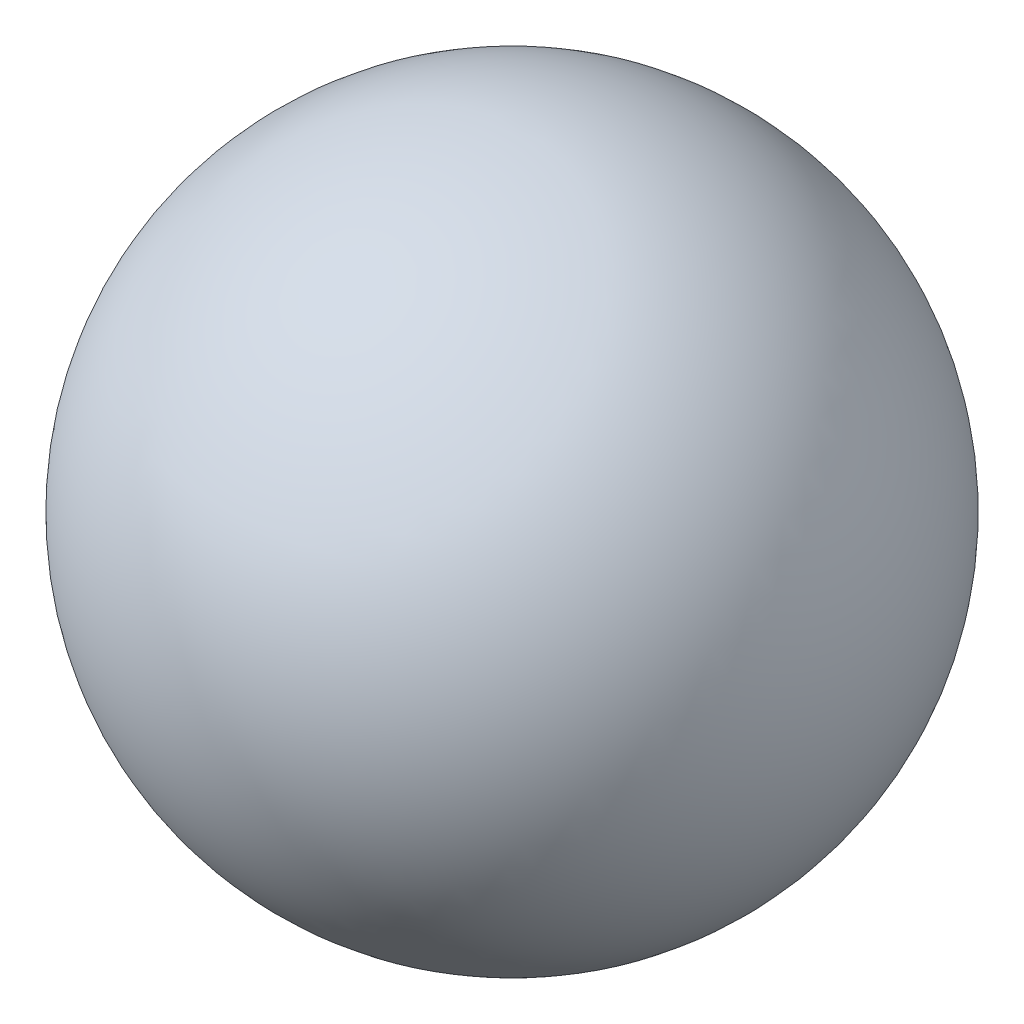
SolidWorks part; units mm, degrees
ref_plane "前视基准面" through (0, 0, 0) normal (0, 0, 1) x (1, 0, 0)
ref_plane "上视基准面" through (0, 0, 0) normal (0, 1, 0) x (1, 0, 0)
ref_plane "右视基准面" through (0, 0, 0) normal (1, 0, 0) x (0, 0, -1)
sketch "草图1" plane through (0, 0, 0) normal (0, 0, 1) x (1, 0, 0)
  line L0 (0, 27.1796) -> (0, -33.9565) construction
  line L1 (0, 21) -> (0, -21)
  arc A0 (0, -21) -> (0, 21) centre (0, 0) ccw
  point P5 (0, 0)
  point P6 (0, -33.9565)
  point P7 (0, 21)
  point P8 (0, 27.1796)
  dimension "D1" = 42
revolve "旋转6" add sketch "草图1" angle 360 about L0
